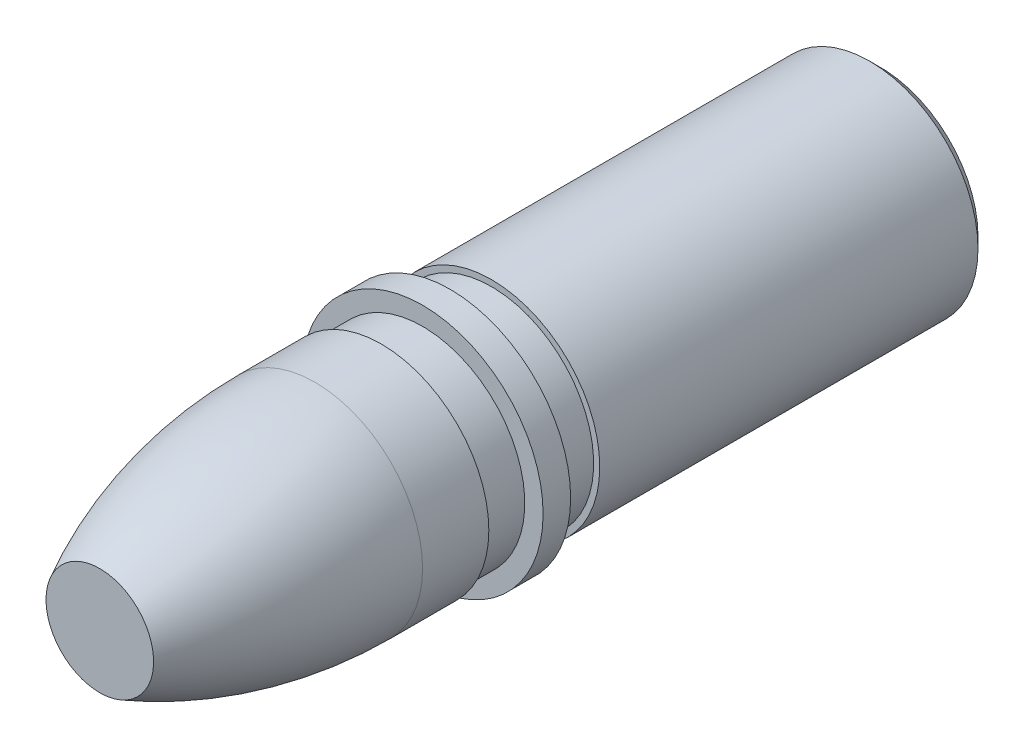
SolidWorks part; units mm, degrees
ref_plane "Front" through (0, 0, 0) normal (0, 0, 1) x (1, 0, 0)
ref_plane "Top" through (0, 0, 0) normal (0, 1, 0) x (1, 0, 0)
ref_plane "Right" through (0, 0, 0) normal (1, 0, 0) x (0, 0, -1)
sketch "Sketch1" plane through (0, 0, 0) normal (1, 0, 0) x (0, 0, -1)
  line L0 (0, 0) -> (0, 1.5875)
  line L2 (6.35, 3.1737) -> (8.3058, 3.1737)
  line L3 (9.525, 3.015) -> (9.525, 3.556)
  line L4 (9.525, 3.556) -> (10.3378, 3.556)
  line L5 (10.3378, 3.556) -> (10.3378, 3.015)
  line L6 (10.3378, 3.015) -> (11.557, 3.015)
  line L7 (11.557, 3.015) -> (11.557, 3.1953)
  line L8 (11.557, 3.1953) -> (23.0378, 3.1953)
  line L9 (23.0378, 3.1953) -> (23.0378, 0)
  line L10 (23.0378, 0) -> (0, 0)
  line L11 (0, 0) -> (-3.0107, 0) construction
  line L12 (9.525, 3.015) -> (8.3058, 3.015)
  line L13 (8.3058, 3.015) -> (8.3058, 3.1737)
  arc A0 (6.35, 3.1737) -> (0, 1.5875) centre (6.35, -10.3296) ccw
  dimension "D8" = 1.2192
  dimension "End Diameter" = 3.175
  dimension "Head Straight" = 3.175
  dimension "Head Height | B" = 9.525
  dimension "Shank Height | D" = 12.7
  dimension "Overall Height" = 23.0378
  dimension "Shoulder Height" = 0.8128
  dimension "D1" = 0.1587
  dimension "Shank Diameter | C" = 6.3906
  dimension "Head Diameter | A" = 6.3475
  dimension "Shoulder Diameter" = 7.112
sketch "Sketch2" plane through (0, 0, 0) normal (1, 0, 0) x (0, 0, -1)
  line L0 (0, 0) -> (0, 1.5875)
  line L1 (9.525, 3.015) -> (8.3058, 3.015) construction
  line L2 (6.35, 3.1737) -> (8.3058, 3.1737)
  line L3 (9.525, 3.015) -> (9.525, 3.556)
  line L4 (9.525, 3.556) -> (10.3378, 3.556)
  line L5 (10.3378, 3.556) -> (10.3378, 3.015)
  line L6 (10.3378, 3.015) -> (11.557, 3.015)
  line L7 (11.557, 3.015) -> (11.557, 3.1953)
  line L8 (11.557, 3.1953) -> (23.0378, 3.1953)
  line L9 (23.0378, 3.1953) -> (23.0378, 0)
  line L10 (23.0378, 0) -> (0, 0)
  line L11 (0, 0) -> (-3.0107, 0) construction
  line L12 (9.525, 3.015) -> (8.3058, 3.015)
  line L13 (8.3058, 3.015) -> (8.3058, 3.1737)
  line L14 (8.3058, 3.015) -> (8.3058, 3.1737) construction
  arc A0 (6.35, 3.1737) -> (0, 1.5875) centre (6.35, -10.3296) ccw
  dimension "D1" = 3.175
  dimension "A" = 6.3475
  dimension "D3" = 3.175
  dimension "C" = 9.525
  dimension "E" = 12.7
  dimension "D" = 23.0378
  dimension "B" = 6.3906
  dimension "D8" = 1.2192
  dimension "F" = 7.112
  dimension "G" = 0.8128
revolve "Revolve1" add sketch "Sketch2" angle 360 about L11
chamfer "Chamfer1" distance 0.3195 angle 45 1 edges at (-3.1953, 0, -23.0378)
equation "\"D8@Sketch2\" = \"D8@Sketch1\""
equation "\"D1@Chamfer1\" = \"B@Sketch2\" * .05"
equation "\"D8@Sketch1\" = \"Shoulder Height@Sketch1\" * 1.5"
equation "\"D1@Sketch1\"= \"Head Diameter | A@Sketch1\" / 40"
equation "\"A@Sketch2\"=\"Head Diameter | A@Sketch1\""
equation "\"F@Sketch2\"=\"Shoulder Diameter@Sketch1\""
equation "\"D1@Sketch2\"=\"End Diameter@Sketch1\""
equation "\"C@Sketch2\"=\"Head Height | B@Sketch1\""
equation "\"B@Sketch2\"=\"Shank Diameter | C@Sketch1\""
equation "\"D3@Sketch2\"=\"Head Straight@Sketch1\""
equation "\"E@Sketch2\"=\"Shank Height | D@Sketch1\""
equation "\"G@Sketch2\"=\"Shoulder Height@Sketch1\""
